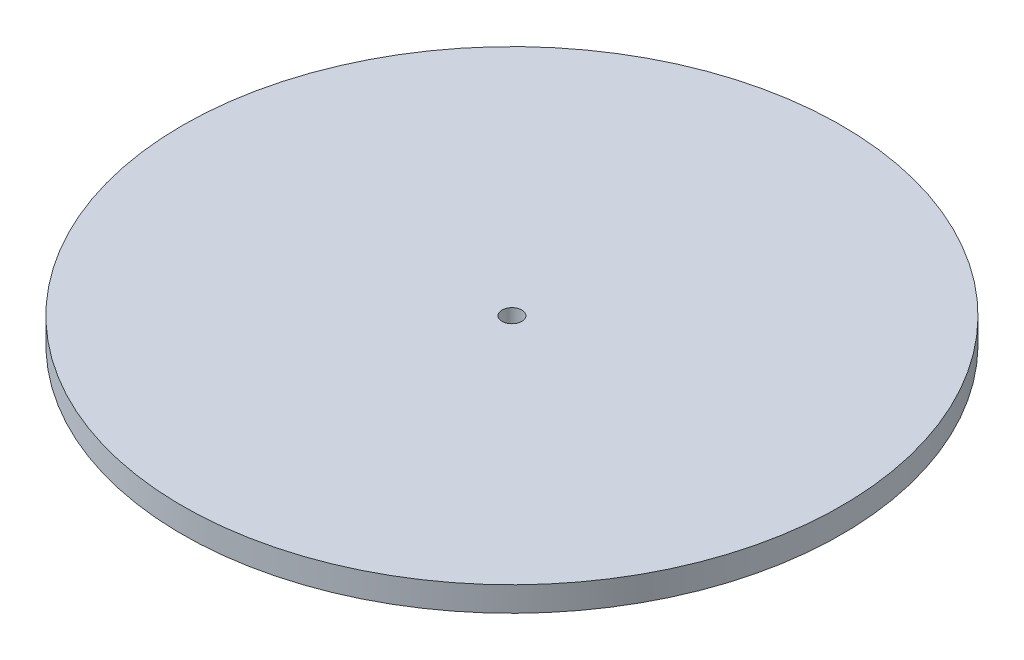
SolidWorks part; units mm, degrees
ref_plane "Front Plane" through (0, 0, 0) normal (0, 0, 1) x (1, 0, 0)
ref_plane "Top Plane" through (0, 0, 0) normal (0, 1, 0) x (1, 0, 0)
ref_plane "Right Plane" through (0, 0, 0) normal (1, 0, 0) x (0, 0, -1)
sketch "Sketch3" plane through (0, 0, 0) normal (0, 0, 1) x (1, 0, 0)
  line L0 (37, 19.9472) -> (37, 23.9472) construction
  line L1 (37, 23.9472) -> (0, 23.9472) construction
  line L2 (0, 23.9472) -> (0, 0) construction
  line L4 (1.2, 23.9472) -> (1.2, 18.9472)
  line L5 (1.2, 18.9472) -> (0, 18.9472)
  line L6 (0, 18.9472) -> (0, 0)
  line L7 (37, 19.9472) -> (40, 19.9472) construction
  line L8 (40, 19.9472) -> (40, 23.9472) construction
  line L9 (40, 23.9472) -> (1.2, 23.9472)
  line L10 (37, 19.9472) -> (37, 20.9472)
  line L11 (37, 20.9472) -> (40, 20.9472)
  line L12 (40, 20.9472) -> (40, 23.9472)
  spline S0 degree 9 poles (-3.5027, 1.7242) (1.4082, -3.8344) (6.3191, 3.5563) (11.23, 4.3712) (16.1409, 8.0977) (21.0518, 11.6912) (25.9627, 13.3814) (30.8736, 17.1742) (35.7845, 19.1017) (40.6954, 21.9737) knots 0 0 0 0 0 0 0 0 0 0 1 1 1 1 1 1 1 1 1 1 construction
  spline S1 degree 9 poles (0, 0) (4.1111, -0.0662) (8.2222, 3.5767) (12.3333, 5.5728) (16.4444, 8.2843) (20.5556, 10.9694) (24.6667, 13.0805) (28.7778, 15.5994) (32.8889, 17.76) (37, 19.9472) knots 0.07925 0.07925 0.07925 0.07925 0.07925 0.07925 0.07925 0.07925 0.07925 0.07925 0.91639 0.91639 0.91639 0.91639 0.91639 0.91639 0.91639 0.91639 0.91639 0.91639
  dimension "D1" = 3
  dimension "D2" = 1.2
  dimension "D3" = 5
  dimension "D4" = 3
  dimension "D5" = 40
  dimension "D6" = 19.9472
  dimension "D7" = 37
  dimension "D8" = 4
revolve "Revolve4" add sketch "Sketch3" angle 360 about L2
sketch "Sketch5" plane through (0, 23.9472, 0) normal (0, 1, 0) x (1, 0, 0)
  circle A0 centre (0, 0) radius 1.2
  circle A2 centre (0, 0) radius 1.2 construction
extrude "Cut-Extrude1" cut sketch "Sketch5" against normal through all
